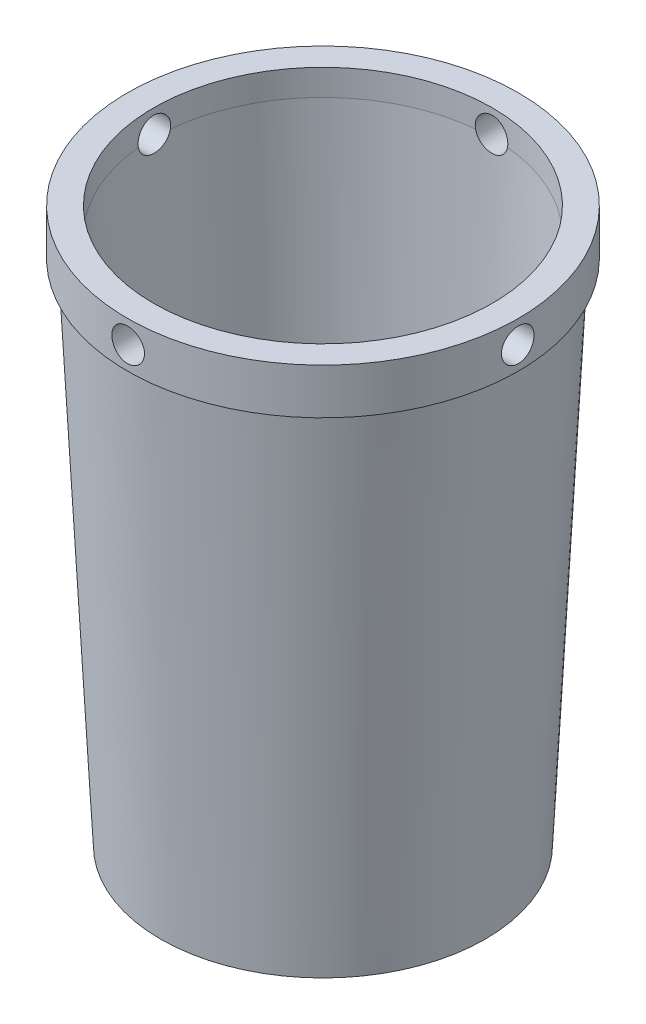
SolidWorks part; units mm, degrees
ref_plane "Front Plane" through (0, 0, 0) normal (0, 0, 1) x (1, 0, 0)
ref_plane "Top Plane" through (0, 0, 0) normal (0, 1, 0) x (1, 0, 0)
ref_plane "Right Plane" through (0, 0, 0) normal (1, 0, 0) x (0, 0, -1)
sketch "Sketch2" plane through (0, 0, 0) normal (0, 0, 1) x (1, 0, 0)
  line L0 (0, 0) -> (0, 107.95) construction
  line L1 (0, 0) -> (27.3304, 0) construction
  line L2 (0, 0) -> (31.623, 0)
  line L3 (0, 107.95) -> (38.0746, 107.95) construction
  line L4 (27.3304, 0) -> (27.3304, 2.54)
  line L5 (27.3304, 2.54) -> (29.083, 2.54)
  line L6 (31.623, 0) -> (36.4998, 99.06)
  line L7 (38.0746, 107.95) -> (32.9946, 107.95)
  line L8 (32.9946, 107.95) -> (32.9946, 102.87)
  line L9 (32.9946, 102.87) -> (29.083, 2.54)
  line L10 (38.0746, 107.95) -> (38.0746, 99.06)
  line L11 (38.0746, 99.06) -> (36.4998, 99.06)
  point P11 (0, 0)
  point P13 (0, 0)
  dimension "D1" = 31.623
  dimension "D2" = 27.3304
  dimension "D3" = 107.95
  dimension "D4" = 108.1426
  dimension "D5" = 100.33
  dimension "D6" = 32.9946
  dimension "D7" = 100.4062
revolve "Revolve2" add sketch "Sketch2" angle 360 about L0
sketch "Sketch5" plane through (0, 0, 0) normal (0, 0, 1) x (1, 0, 0)
  line L0 (0, 107.95) -> (0, 99.06)
  line L1 (32.9946, 107.95) -> (-32.9946, 107.95) construction
  line L2 (-36.4998, 99.06) -> (36.4998, 99.06) construction
  circle A0 centre (0, 103.505) radius 3.175
extrude "Cut-Extrude2" cut sketch "Sketch5" against normal blind 45.212 contours L0 A0 | L0 A0
pattern_circular "CirPattern2" count 4 over 360 about axis through (0, 0, 0) along (0, -1, 0) of "Cut-Extrude2"
